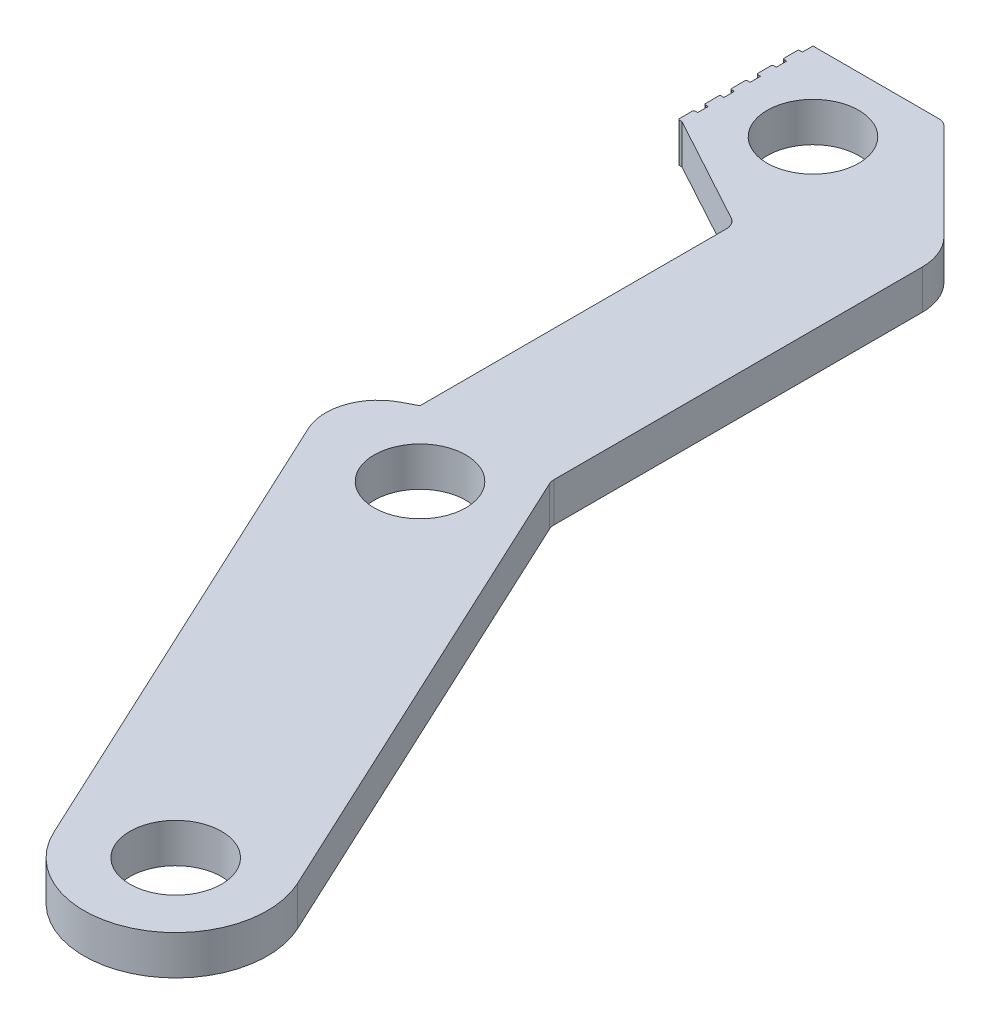
SolidWorks part; units mm, degrees
material "1023 Carbon Steel Sheet (SS)"
ref_plane "Front Plane" through (0, 0, 0) normal (0, 0, 1) x (1, 0, 0)
ref_plane "Top Plane" through (0, 0, 0) normal (0, 1, 0) x (1, 0, 0)
ref_plane "Right Plane" through (0, 0, 0) normal (1, 0, 0) x (0, 0, -1)
sketch "Sketch1" plane through (0, 0, 0) normal (0, 1, 0) x (1, 0, 0)
  line L0 (-2.5, 12) -> (-2.5, 0)
  line L1 (-2.5, 0) -> (-4.6894, -1.1457)
  line L2 (-4.6894, -1.1457) -> (4.6082, -21.0845)
  line L4 (10.9524, -18.1262) -> (2.5, 0)
  line L5 (2.5, 0) -> (2.5, 15)
  line L6 (2.5, 15) -> (-1.8912, 19.3912)
  line L7 (-1.8912, 19.3912) -> (-6.8912, 19.3912)
  line L8 (-6.8912, 19.3912) -> (-6.8912, 14.3912)
  line L9 (-6.8912, 14.3912) -> (-2.5, 12)
  arc A0 (10.9524, -18.1262) -> (4.6082, -21.0845) centre (7.7803, -19.6053) cw
  circle A1 centre (-3.8912, 16.3912) radius 1.75
  circle A2 centre (0, -2.5) radius 1.75
  circle A3 centre (7.7803, -19.6053) radius 1.75
  dimension "D3" = 7
  dimension "D11" = 5
  dimension "D13" = 3.5
  dimension "D16" = 3.5
  dimension "D19" = 3.5
  dimension "D1" = 5
  dimension "D2" = 20
  dimension "D4" = 205
  dimension "D5" = 22
  dimension "D6" = 15
  dimension "D7" = 12
  dimension "D8" = 225
  dimension "D9" = 5
  dimension "D10" = 5
  dimension "D12" = 2.5
  dimension "D14" = 3
  dimension "D15" = 3
  dimension "D17" = 2.5
  dimension "D18" = 2.5
extrude "Boss-Extrude1" add sketch "Sketch1" along normal mid plane 1.5
fillet "Fillet1" radius 2 2 edges at (2.5, 0, -15) (-4.6894, 0, 1.1457)
fillet "Fillet2" radius 0.5 3 edges at (-2.5, 0, -12) (-1.8912, 0, -19.3912) (2.5, 0, 0)
sketch "Sketch2" plane through (-6.8912, 0, 0) normal (-1, 0, 0) x (0, 0, 1)
  line L0 (-19.3912, 0.75) -> (-14.3912, 0.75) construction
  line L1 (-14.9912, 0.75) -> (-14.3912, 0.75)
  line L2 (-14.9912, 0.75) -> (-14.9912, -0.75)
  line L3 (-14.9912, -0.75) -> (-14.3912, -0.75)
  line L4 (-14.3912, 0.75) -> (-14.3912, -0.75)
  line L5 (-15.9912, 0.75) -> (-15.9912, -0.75)
  line L6 (-15.9912, 0.75) -> (-15.3912, 0.75)
  line L7 (-15.3912, 0.75) -> (-15.3912, -0.75)
  line L8 (-15.9912, -0.75) -> (-15.3912, -0.75)
  line L9 (-16.9912, 0.75) -> (-16.9912, -0.75)
  line L10 (-16.9912, 0.75) -> (-16.3912, 0.75)
  line L11 (-16.3912, 0.75) -> (-16.3912, -0.75)
  line L12 (-16.9912, -0.75) -> (-16.3912, -0.75)
  line L13 (-17.9912, 0.75) -> (-17.9912, -0.75)
  line L14 (-17.9912, 0.75) -> (-17.3912, 0.75)
  line L15 (-17.3912, 0.75) -> (-17.3912, -0.75)
  line L16 (-17.9912, -0.75) -> (-17.3912, -0.75)
  line L17 (-18.9912, 0.75) -> (-18.9912, -0.75)
  line L18 (-18.9912, 0.75) -> (-18.3912, 0.75)
  line L19 (-18.3912, 0.75) -> (-18.3912, -0.75)
  line L20 (-18.9912, -0.75) -> (-18.3912, -0.75)
  dimension "D1" = 0.6
  dimension "D2" = 5
extrude "Boss-Extrude2" add sketch "Sketch2" along normal blind 0.15
fillet "Fillet3" radius 0.05 10 edges at (-7.0412, 0, -16.9912) (-7.0412, 0, -17.9912) (-7.0412, 0, -14.3912) (-7.0412, 0, -14.9912) (-7.0412, 0, -15.3912) (-7.0412, 0, -15.9912) (-7.0412, 0, -16.3912) (-7.0412, 0, -17.3912) (-7.0412, 0, -18.3912) (-7.0412, 0, -18.9912)
